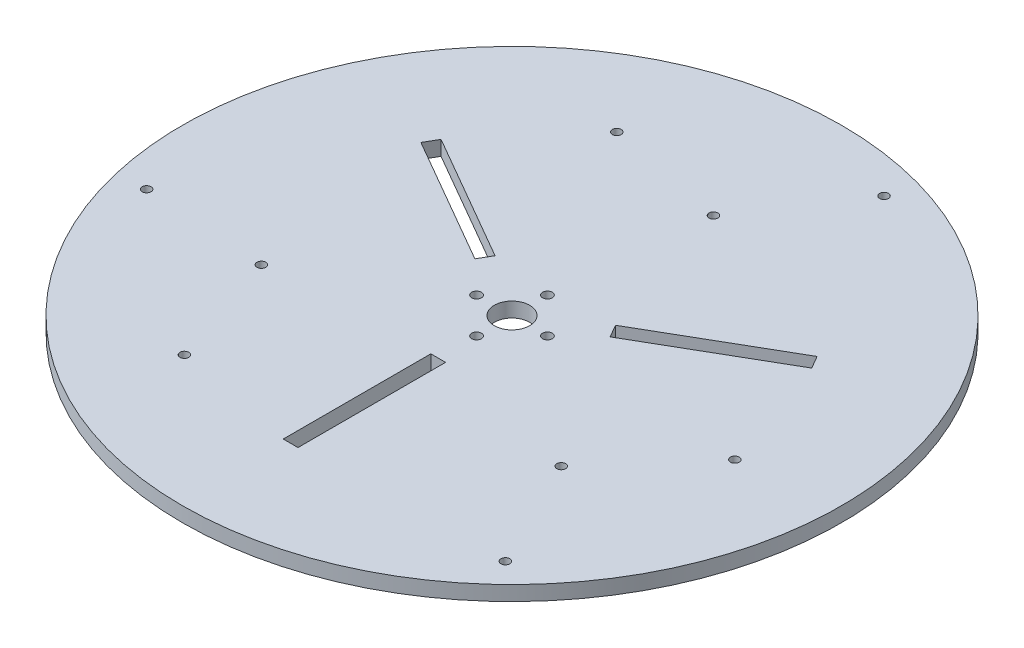
SolidWorks part; units mm, degrees
ref_plane "前基準面" through (0, 0, 0) normal (0, 0, 1) x (1, 0, 0)
ref_plane "上基準面" through (0, 0, 0) normal (0, 1, 0) x (1, 0, 0)
ref_plane "右基準面" through (0, 0, 0) normal (1, 0, 0) x (0, 0, -1)
sketch "草圖1" plane through (0, 0, 0) normal (0, 1, 0) x (1, 0, 0)
  line L2 (0, 75) -> (0, 0) construction
  line L3 (-64.9519, -37.5) -> (0, 0) construction
  line L4 (-28.5, 28.5) -> (28.5, 28.5) construction
  line L5 (-28.5, 28.5) -> (-28.5, -28.5) construction
  line L6 (-28.5, -28.5) -> (28.5, -28.5) construction
  line L7 (28.5, 28.5) -> (28.5, -28.5) construction
  line L8 (0, 0) -> (64.9519, -37.5) construction
  arc A20 (-54.1401, 84.0764) -> (-99.8824, 4.8485) centre (0, 0) ccw
  arc A21 (-37.5, 75) -> (37.5, 75) centre (0, 75) ccw
  circle A24 centre (0, 0) radius 6
  arc A25 (83.7019, -5.024) -> (46.2019, -69.976) centre (64.9519, -37.5) ccw
  arc A26 (-46.2019, -69.976) -> (-83.7019, -5.024) centre (-64.9519, -37.5) ccw
  arc A27 (99.8824, 4.8485) -> (54.1401, 84.0764) centre (0, 0) ccw
  arc A28 (-45.7423, -88.9249) -> (45.7423, -88.9249) centre (0, 0) ccw
  arc A29 (-54.1401, 84.0764) -> (-37.5, 75) centre (-48.2955, 75) cw
  arc A30 (54.1401, 84.0764) -> (37.5, 75) centre (48.2955, 75) ccw
  arc A31 (99.8824, 4.8485) -> (83.7019, -5.024) centre (89.0996, 4.3251) cw
  arc A32 (45.7423, -88.9249) -> (46.2019, -69.976) centre (40.8042, -79.3251) ccw
  arc A33 (-45.7423, -88.9249) -> (-46.2019, -69.976) centre (-40.8042, -79.3251) cw
  arc A34 (-99.8824, 4.8485) -> (-83.7019, -5.024) centre (-89.0996, 4.3251) ccw
  point P16 (0, 28.5)
  point P18 (-28.5, 0)
  dimension "D1" = 75
  dimension "D2" = 200
  dimension "D3" = 75
  dimension "D4" = 12
  dimension "D6" = 3
  dimension "D5" = 57
extrude "填料-伸長1" add sketch "草圖1" against normal blind 5
sketch "草圖5" plane through (0, 0, 0) normal (0, 1, 0) x (1, 0, 0)
  line L0 (0, 75) -> (-26.5165, 48.4835) construction
  line L1 (0, 75) -> (0, 0) construction
  line L2 (-63.7019, 39.6651) -> (-66.2019, 35.3349)
  line L3 (-63.7019, 39.6651) -> (-20.4006, 14.6651)
  line L4 (-66.2019, 35.3349) -> (-22.9006, 10.3349)
  line L5 (-20.4006, 14.6651) -> (-22.9006, 10.3349)
  line L6 (-21.6506, 12.5) -> (0, 0) construction
  line L7 (66.2019, 35.3349) -> (63.7019, 39.6651)
  line L8 (66.2019, 35.3349) -> (22.9006, 10.3349)
  line L9 (63.7019, 39.6651) -> (20.4006, 14.6651)
  line L10 (22.9006, 10.3349) -> (20.4006, 14.6651)
  line L11 (-2.5, -75) -> (2.5, -75)
  line L12 (-2.5, -75) -> (-2.5, -25)
  line L13 (2.5, -75) -> (2.5, -25)
  line L14 (-2.5, -25) -> (2.5, -25)
  arc A0 (-37.5, 75) -> (37.5, 75) centre (0, 75) ccw construction
  arc A1 (-37.5, 75) -> (37.5, 75) centre (0, 75) ccw construction
  arc A2 (-94.4114, 32.962) -> (-26.5165, 48.4835) centre (-55.5913, 19.4087) cw
  arc A3 (-54.1401, 84.0764) -> (-99.8824, 4.8485) centre (0, 0) ccw construction
  arc A4 (-37.5, 75) -> (-54.1401, 84.0764) centre (-48.2955, 75) ccw construction
  arc A5 (-37.5, 75) -> (-54.1401, 84.0764) centre (-48.2955, 75) ccw
  arc A6 (-54.1401, 84.0764) -> (-99.8824, 4.8485) centre (0, 0) ccw construction
  arc A7 (-94.4114, 32.962) -> (-54.1401, 84.0764) centre (0, 0) cw
  arc A8 (-37.5, 75) -> (-26.5165, 48.4835) centre (0, 75) ccw
  arc A9 (83.7019, -5.024) -> (99.8824, 4.8485) centre (89.0996, 4.3251) ccw
  arc A10 (83.7019, -5.024) -> (55.2462, -1.2778) centre (64.9519, -37.5) ccw
  arc A11 (75.7516, 65.2816) -> (55.2462, -1.2778) centre (44.6041, 38.4391) cw
  arc A12 (75.7516, 65.2816) -> (99.8824, 4.8485) centre (0, 0) cw
  arc A13 (-46.2019, -69.976) -> (-45.7423, -88.9249) centre (-40.8042, -79.3251) ccw
  arc A14 (-46.2019, -69.976) -> (-28.7297, -47.2057) centre (-64.9519, -37.5) ccw
  arc A15 (18.6598, -98.2436) -> (-28.7297, -47.2057) centre (10.9872, -57.8478) cw
  arc A16 (18.6598, -98.2436) -> (-45.7423, -88.9249) centre (0, 0) cw
  dimension "D2" = 3
  dimension "D1" = 45
  dimension "D3" = 60
  dimension "D4" = 50
  dimension "D5" = 5
  dimension "D6" = 25
extrude "除料-伸長1" cut sketch "草圖5" against normal through all both and the other way through all contours A16 A15 A14 A13 | A12 A11 A10 A9 | L5 L3 L2 L4 | L14 L12 L11 L13 | L10 L8 L7 L9 | A8 A5 A7 A2
sketch "草圖2" plane through (0, 0, 0) normal (0, 1, 0) x (1, 0, 0)
  line L0 (-12, 0) -> (12, 0)
  line L1 (0, -12) -> (0, 12)
  point P4 (0, 0)
  point P5 (0, 0)
  dimension "D1" = 24
sketch "草圖6" plane through (0, 0, 0) normal (0, 1, 0) x (1, 0, 0)
  line L0 (-83.7019, -5.024) -> (-64.9519, -37.5)
  line L1 (-64.9519, -37.5) -> (-28.7297, -47.2057)
  line L2 (-80.1709, -57.3338) -> (-57.3424, -27.5831) construction
  line L3 (-98.9209, -24.8579) -> (-80.1709, -57.3338) construction
  line L4 (-80.1709, -57.3338) -> (-43.9487, -67.0395) construction
  line L5 (-98.9209, -24.8579) -> (-107.5812, -29.8579)
  arc A0 (52.658, 8.3815) -> (68.1765, 58.7535) centre (44.6041, 38.4391) ccw construction
  arc A1 (68.1765, 58.7535) -> (48.7261, 75.6688) centre (0, 0) ccw construction
  arc A2 (48.7261, 75.6688) -> (47.5, 75) centre (48.2955, 75) ccw construction
  arc A3 (-33.5876, 41.4124) -> (47.5, 75) centre (0, 75) ccw construction
  arc A4 (-33.5876, 41.4124) -> (-84.9702, 29.6658) centre (-55.5913, 19.4087) ccw construction
  arc A5 (-84.9702, 29.6658) -> (-89.8942, 4.3637) centre (0, 0) ccw construction
  arc A6 (-89.8942, 4.3637) -> (-88.7019, 3.6362) centre (-89.0996, 4.3251) ccw construction
  arc A7 (-19.0704, -49.7939) -> (-88.7019, 3.6362) centre (-64.9519, -37.5) ccw construction
  arc A8 (-19.0704, -49.7939) -> (16.7938, -88.4193) centre (10.9872, -57.8478) ccw construction
  arc A9 (16.7938, -88.4193) -> (41.168, -80.0324) centre (0, 0) ccw construction
  arc A10 (41.168, -80.0324) -> (41.2019, -78.6362) centre (40.8042, -79.3251) ccw construction
  arc A11 (52.658, 8.3815) -> (41.2019, -78.6362) centre (64.9519, -37.5) ccw construction
  arc A12 (55.2462, -1.2778) -> (75.7516, 65.2816) centre (44.6041, 38.4391) ccw
  arc A14 (55.2462, -1.2778) -> (75.7516, 65.2816) centre (44.6041, 38.4391) ccw
  arc A16 (75.7516, 65.2816) -> (54.1401, 84.0764) centre (0, 0) ccw
  arc A18 (75.7516, 65.2816) -> (54.1401, 84.0764) centre (0, 0) ccw
  arc A20 (54.1401, 84.0764) -> (37.5, 75) centre (48.2955, 75) ccw
  arc A22 (54.1401, 84.0764) -> (37.5, 75) centre (48.2955, 75) ccw
  arc A36 (-43.9487, -67.0395) -> (-98.9209, -24.8579) centre (-80.1709, -57.3338) ccw construction
  circle A37 centre (0, 0) radius 111.6477
  arc A48 (-26.5165, 48.4835) -> (37.5, 75) centre (0, 75) ccw
  arc A50 (-26.5165, 48.4835) -> (37.5, 75) centre (0, 75) ccw
  arc A52 (-26.5165, 48.4835) -> (-94.4114, 32.962) centre (-55.5913, 19.4087) ccw
  arc A54 (-26.5165, 48.4835) -> (-94.4114, 32.962) centre (-55.5913, 19.4087) ccw
  arc A56 (-94.4114, 32.962) -> (-99.8824, 4.8485) centre (0, 0) ccw
  arc A58 (-94.4114, 32.962) -> (-99.8824, 4.8485) centre (0, 0) ccw
  arc A60 (-99.8824, 4.8485) -> (-83.7019, -5.024) centre (-89.0996, 4.3251) ccw
  arc A61 (-99.8824, 4.8485) -> (-83.7019, -5.024) centre (-89.0996, 4.3251) ccw
  arc A62 (-28.7297, -47.2057) -> (-83.7019, -5.024) centre (-64.9519, -37.5) ccw
  arc A63 (-28.7297, -47.2057) -> (-83.7019, -5.024) centre (-64.9519, -37.5) ccw
  arc A64 (-28.7297, -47.2057) -> (18.6598, -98.2436) centre (10.9872, -57.8478) ccw
  arc A65 (-28.7297, -47.2057) -> (18.6598, -98.2436) centre (10.9872, -57.8478) ccw
  arc A66 (18.6598, -98.2436) -> (45.7423, -88.9249) centre (0, 0) ccw
  arc A67 (18.6598, -98.2436) -> (45.7423, -88.9249) centre (0, 0) ccw
  arc A68 (45.7423, -88.9249) -> (46.2019, -69.976) centre (40.8042, -79.3251) ccw
  arc A69 (45.7423, -88.9249) -> (46.2019, -69.976) centre (40.8042, -79.3251) ccw
  arc A70 (55.2462, -1.2778) -> (46.2019, -69.976) centre (64.9519, -37.5) ccw
  arc A71 (55.2462, -1.2778) -> (46.2019, -69.976) centre (64.9519, -37.5) ccw
  point P48 (-62.5263, 49.7441)
  point P49 (18.1775, 31.1157)
  point P50 (74.3428, 29.2773)
  point P51 (17.8583, -31.3)
  point P52 (-11.8165, -79.0214)
  point P53 (-36.0357, 0.1843)
  point P55 (-19.0704, -49.7939)
  point P56 (52.658, 8.3815)
  point P57 (41.2019, -78.6362)
  point P58 (47.5, 75)
  point P59 (-33.5876, 41.4124)
  arc M38 (55.2462, -1.2778) -> (75.7516, 65.2816) centre (44.6041, 38.4391) ccw
  arc M39 (75.7516, 65.2816) -> (54.1401, 84.0764) centre (0, 0) ccw
  arc M40 (54.1401, 84.0764) -> (37.5, 75) centre (48.2955, 75) ccw
  arc M41 (37.5, 75) -> (-26.5165, 48.4835) centre (0, 75) cw
  arc M42 (-26.5165, 48.4835) -> (-94.4114, 32.962) centre (-55.5913, 19.4087) ccw
  arc M43 (-94.4114, 32.962) -> (-99.8824, 4.8485) centre (0, 0) ccw
  arc M44 (-99.8824, 4.8485) -> (-83.7019, -5.024) centre (-89.0996, 4.3251) ccw
  arc M45 (-83.7019, -5.024) -> (-28.7297, -47.2057) centre (-64.9519, -37.5) cw
  arc M46 (-28.7297, -47.2057) -> (18.6598, -98.2436) centre (10.9872, -57.8478) ccw
  arc M47 (18.6598, -98.2436) -> (45.7423, -88.9249) centre (0, 0) ccw
  arc M48 (45.7423, -88.9249) -> (46.2019, -69.976) centre (40.8042, -79.3251) ccw
  arc M49 (46.2019, -69.976) -> (55.2462, -1.2778) centre (64.9519, -37.5) cw
  dimension "D3" = 10
  dimension "D2" = 67.5
  dimension "D4" = 25
  dimension "D1" = 0
extrude "填料-伸長4" add sketch "草圖6" against normal up to surface (5 mm away) contours A37 L1 L0 M44 M43 M42 M41 M40 M39 M38 M49 M48 M47 M46 | L0 L1 M45 up to face at (43.3013, -5, -25)
hole_wizard "Ø3.0mm 定位孔1" positions "草圖7" profile "草圖8" hole size "Ø3.0" standard "ISO" end condition up to next
sketch "草圖7" plane through (0, 0, 0) normal (0, 1, 0) x (1, 0, 0)
  point P43 (-43.9487, -67.0395)
  point P46 (-57.3424, -27.5831)
  point P49 (-98.9209, -24.8579)
sketch "草圖8" plane through (-43.9487, 0, 67.0395) normal (1, 0, 0) x (0, 0, 1)
  line L0 (0, 0) -> (0, 5.001)
  line L1 (0, 5.001) -> (1.5, 5.001)
  line L2 (1.5, 5.001) -> (1.5, 0)
  line L5 (1.5, 0) -> (0, 0)
  line L11 (0, -6.35) -> (0, 107.95) construction
  dimension "貫穿孔直徑" = 3
  dimension "貫穿孔深度" = 5.001
pattern_circular "環狀複製排列1" count 3 every 120 about axis through (0, 0, 0) along (0, 1, 0) of "Ø3.0mm 定位孔1"
hole_wizard "M4 螺紋孔1" positions "草圖3" profile "草圖4" tap size "M4" standard "ISO" end condition through all
sketch "草圖3" plane through (0, 0, 0) normal (0, 1, 0) x (1, 0, 0)
  point P0 (0, 12)
  point P3 (12, 0)
  point P6 (0, -12)
  point P9 (-12, 0)
sketch "草圖4" plane through (0, 0, -12) normal (1, 0, 0) x (0, 0, 1)
  line L0 (0, 0) -> (0, 5)
  line L1 (0, 5) -> (1.65, 5)
  line L2 (1.65, 5) -> (1.65, 0)
  line L5 (1.65, 0) -> (0, 0)
  line L11 (0, -6.35) -> (0, 107.95) construction
  dimension "貫穿螺孔鑽直徑" = 3.3
  dimension "貫穿螺孔鑽深度" = 5
cosmetic thread "鑽孔螺紋1" parameters "D2"=4
cosmetic thread "鑽孔螺紋2" parameters "D2"=4
cosmetic thread "鑽孔螺紋3" parameters "D2"=4
cosmetic thread "鑽孔螺紋4" parameters "D2"=4
